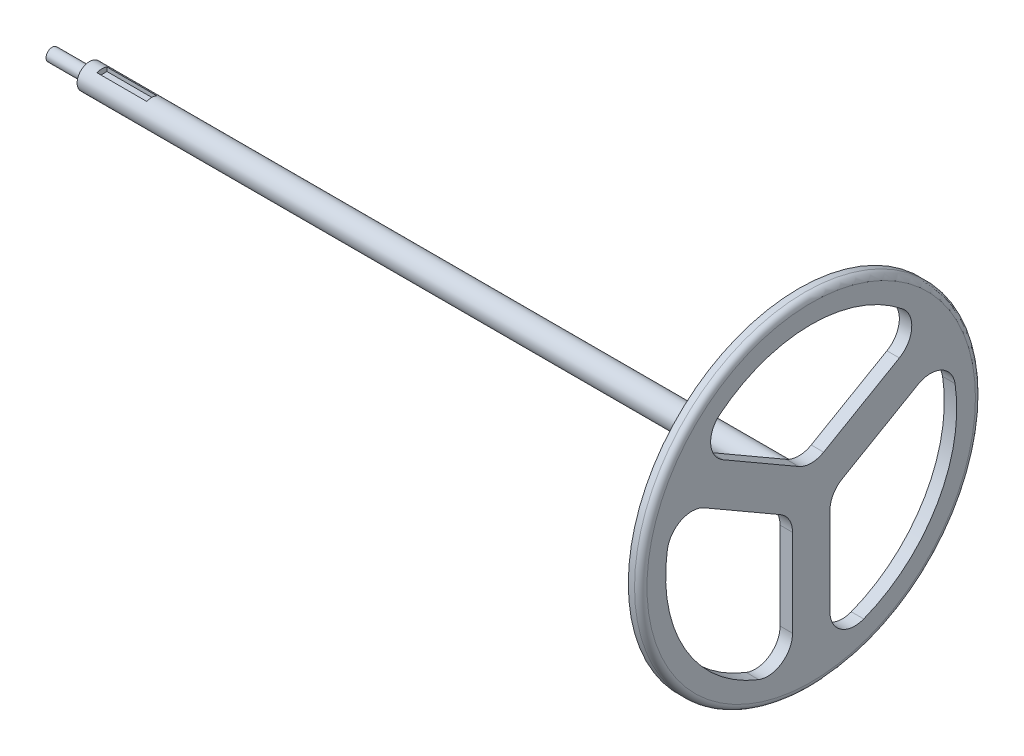
SolidWorks part; units mm, degrees
material "EN8"
ref_plane "Front Plane" through (0, 0, 0) normal (0, 0, 1) x (1, 0, 0)
ref_plane "Top Plane" through (0, 0, 0) normal (0, 1, 0) x (1, 0, 0)
ref_plane "Right Plane" through (0, 0, 0) normal (1, 0, 0) x (0, 0, -1)
sketch "Sketch2" plane through (0, 0, 0) normal (1, 0, 0) x (0, 0, -1)
  circle A0 centre (0, 0) radius 10
  dimension "D1" = 20
extrude "Boss-Extrude1" add sketch "Sketch2" against normal blind 580
sketch "Sketch3" plane through (-580, 0, 0) normal (-1, 0, 0) x (0, 0, 1)
  circle A0 centre (0, 0) radius 5
  dimension "D1" = 10
extrude "Boss-Extrude2" add sketch "Sketch3" along normal blind 30
sketch "Sketch10" plane through (0, 0, 0) normal (0, 1, 0) x (1, 0, 0)
  line L0 (-580, 0) -> (-548.0399, 0)
  line L1 (-580, 10) -> (-580, -10) construction
  dimension "D1" = 31.9601
sketch "Sketch8" plane through (-580, 0, 0) normal (-1, 0, 0) x (0, 0, 1)
  line L0 (0, 10) -> (0, 0) construction
  line L1 (-4, 14) -> (4, 14)
  line L2 (-4, 14) -> (-4, 6)
  line L3 (-4, 6) -> (4, 6)
  line L4 (4, 14) -> (4, 6)
  line L5 (-4, 14) -> (4, 6) construction
  line L6 (-4, 6) -> (4, 14) construction
  circle A0 centre (0, 0) radius 10 construction
  point P0 (0, 10)
  dimension "D1" = 8
  dimension "D2" = 8
extrude "Cut-Extrude1" cut sketch "Sketch8" against normal blind 40 from offset 10 offset against normal yes
sketch "Sketch7" plane through (0, 0, 0) normal (1, 0, 0) x (0, 0, -1)
  line L0 (0, 0) -> (0, -127) construction
  line L1 (0, 0) -> (109.9852, 63.5) construction
  line L2 (0, 0) -> (-109.9852, 63.5) construction
  line L3 (-10, 23.094) -> (-70.8454, 58.2231)
  line L4 (-15, -20.2073) -> (-15, -90.4655)
  line L5 (25, -2.8868) -> (85.8454, 32.2424)
  line L6 (-25, -2.8868) -> (-85.8454, 32.2424)
  line L7 (15, -20.2073) -> (15, -90.4655)
  line L8 (10, 23.094) -> (70.8454, 58.2231)
  line L9 (-116.7154, 50.0652) -> (-117.4852, 50.5096)
  line L10 (-15, 0) -> (-15, -127) construction
  line L11 (-7.5, -12.9904) -> (-117.4852, 50.5096) construction
  line L12 (-7.5, 12.9904) -> (102.4852, 76.4904) construction
  line L13 (7.5, 12.9904) -> (-102.4852, 76.4904) construction
  line L14 (15, 0) -> (15, -127) construction
  line L15 (7.5, -12.9904) -> (117.4852, 50.5096) construction
  line L16 (-101.7154, 76.0459) -> (-102.4852, 76.4904)
  line L17 (-15, -126.1111) -> (-15, -127)
  line L18 (15, -126.1111) -> (15, -127)
  line L19 (116.7154, 50.0652) -> (117.4852, 50.5096)
  line L20 (101.7154, 76.0459) -> (102.4852, 76.4904)
  circle A0 centre (0, 0) radius 127 construction
  circle A1 centre (0, 0) radius 10
  circle A2 centre (0, 0) radius 10 construction
  arc A3 (10, 23.094) -> (-10, 23.094) centre (0, 40.4145) cw
  arc A4 (-15, -20.2073) -> (-25, -2.8868) centre (-35, -20.2073) ccw
  arc A5 (15, -20.2073) -> (25, -2.8868) centre (35, -20.2073) cw
  circle A6 centre (0, 0) radius 137
  arc A7 (-115.6073, 17.9985) -> (-42.2165, -109.1181) centre (0, 0) ccw
  arc A8 (42.2165, -109.1181) -> (115.6073, 17.9985) centre (0, 0) ccw
  circle A9 centre (0, 0) radius 117 construction
  arc A10 (73.3908, 91.1196) -> (-73.3908, 91.1196) centre (0, 0) ccw
  arc A11 (115.6073, 17.9985) -> (85.8454, 32.2424) centre (95.8454, 14.9218) ccw
  arc A12 (73.3908, 91.1196) -> (70.8454, 58.2231) centre (60.8454, 75.5436) cw
  arc A13 (-70.8454, 58.2231) -> (-73.3908, 91.1196) centre (-60.8454, 75.5436) cw
  arc A14 (-85.8454, 32.2424) -> (-115.6073, 17.9985) centre (-95.8454, 14.9218) ccw
  arc A15 (-15, -90.4655) -> (-42.2165, -109.1181) centre (-35, -90.4655) cw
  arc A16 (42.2165, -109.1181) -> (15, -90.4655) centre (35, -90.4655) cw
  point P36 (117, 0)
  dimension "D2" = 254
  dimension "D7" = 20
  dimension "D10" = 20
  dimension "D11" = 20
  dimension "D12" = 20
  dimension "D13" = 20
  dimension "D14" = 20
  dimension "D15" = 20
  dimension "D3" = 120
  dimension "D4" = 120
  dimension "D1" = 0
  dimension "D5" = 15
  dimension "D6" = 15
  dimension "D8" = 10
  dimension "D9" = 10
extrude "Boss-Extrude7" add sketch "Sketch7" against normal blind 10
fillet "Fillet1" radius 5 1 edges at (0, 0, -137)
